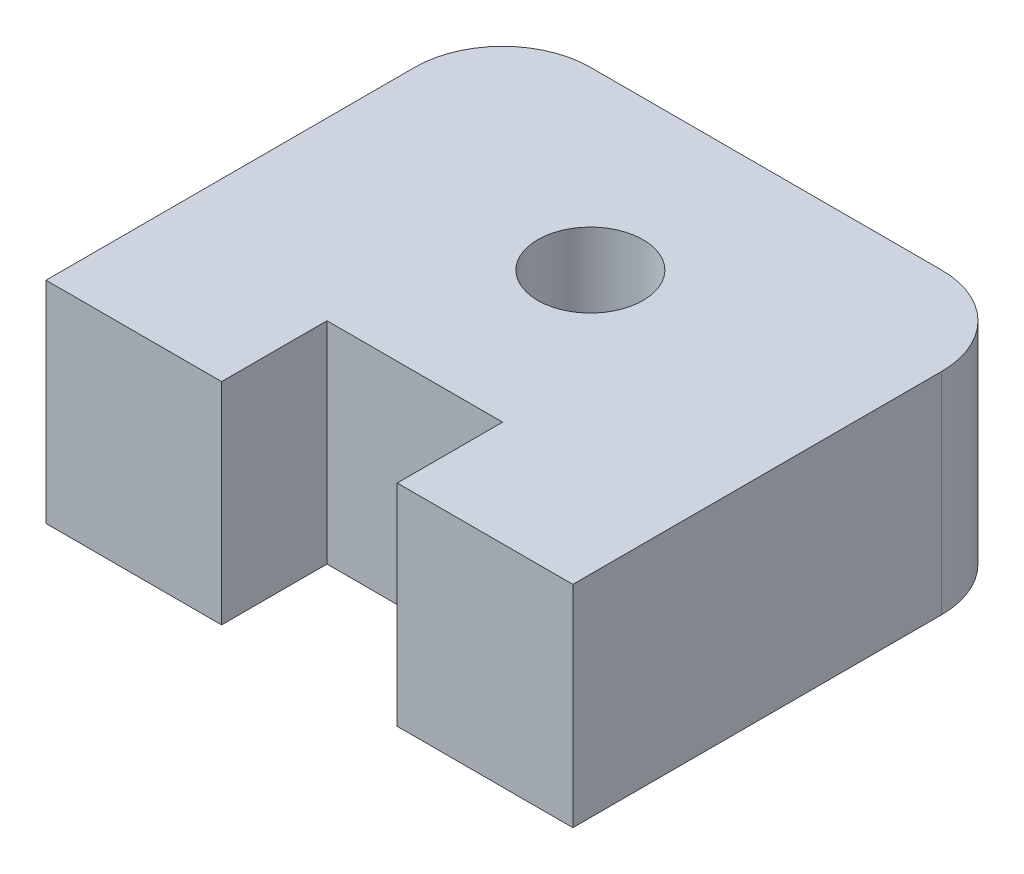
SolidWorks part; units mm, degrees
ref_plane "Front Plane" through (0, 0, 0) normal (0, 0, 1) x (1, 0, 0)
ref_plane "Top Plane" through (0, 0, 0) normal (0, 1, 0) x (1, 0, 0)
ref_plane "Right Plane" through (0, 0, 0) normal (1, 0, 0) x (0, 0, -1)
sketch "Sketch1" plane through (0, 0, 0) normal (0, 1, 0) x (1, 0, 0)
  line L0 (0, 0) -> (0, 10.5)
  line L1 (2.5, 13) -> (12.5, 13)
  line L2 (15, 10.5) -> (15, 0)
  line L3 (15, 0) -> (10, 0)
  line L4 (10, 0) -> (10, 3)
  line L5 (10, 3) -> (5, 3)
  line L6 (5, 3) -> (5, 0)
  line L7 (5, 0) -> (0, 0)
  circle A0 centre (7.5, 8) radius 1.5
  arc A1 (12.5, 13) -> (15, 10.5) centre (12.5, 10.5) cw
  arc A2 (0, 10.5) -> (2.5, 13) centre (2.5, 10.5) cw
  dimension "D5" = 5
  dimension "D6" = 7.5
  dimension "D7" = 3
  dimension "D8" = 2.5
  dimension "D1" = 5
  dimension "D2" = 3
  dimension "D3" = 5
  dimension "D4" = 10
extrude "Boss-Extrude1" add sketch "Sketch1" along normal blind 6
